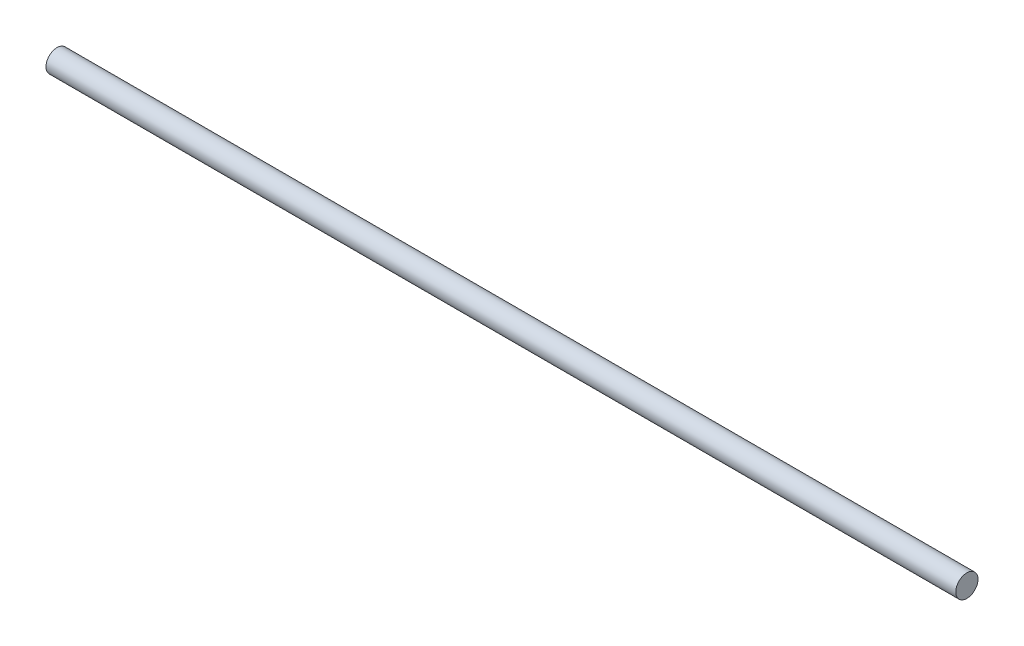
SolidWorks part; units mm, degrees
ref_plane "Front Plane" through (0, 0, 0) normal (0, 0, 1) x (1, 0, 0)
ref_plane "Top Plane" through (0, 0, 0) normal (0, 1, 0) x (1, 0, 0)
ref_plane "Right Plane" through (0, 0, 0) normal (1, 0, 0) x (0, 0, -1)
ref_plane "Plane1" through (-55, 0, 0) normal (1, 0, 0) x (0, 0, -1)
sketch "Sketch1" plane through (-204.5719, 0, 0) normal (-1, 0, 0) x (0, 0, 1)
  circle A0 centre (-1, 149.45) radius 3
  dimension "D1" = 6
extrude "Boss-Extrude1" add sketch "Sketch1" along normal up to surface (245.4281 mm away)
